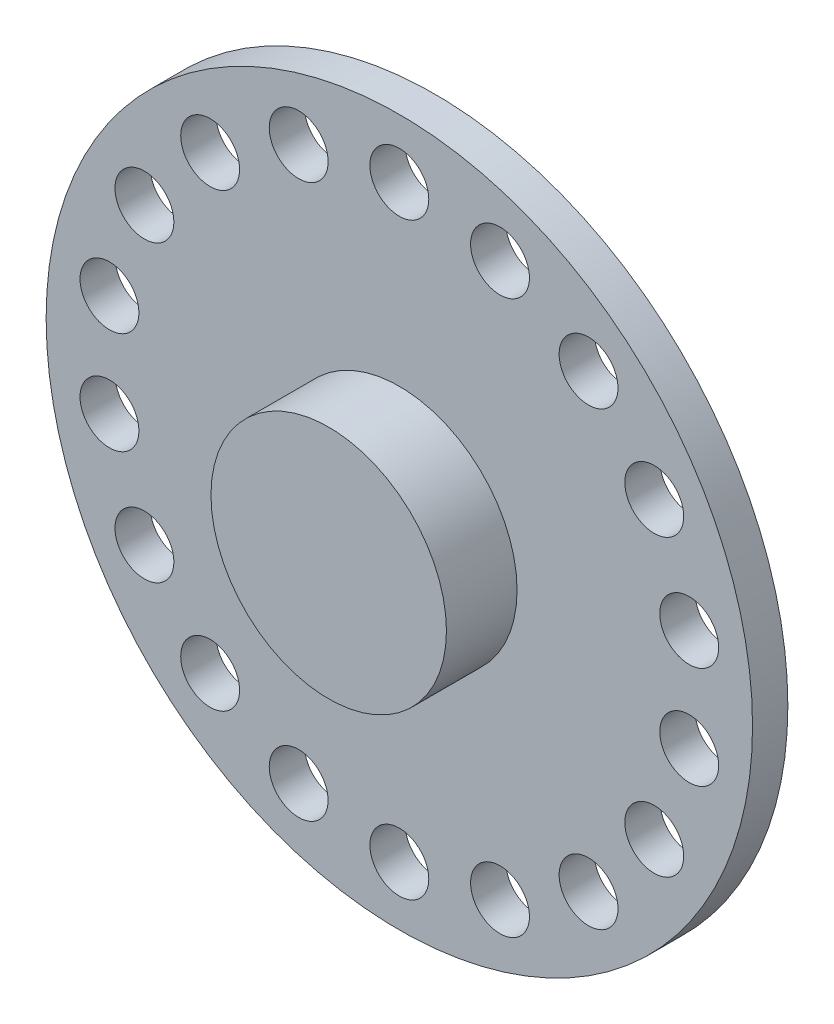
SolidWorks part; units mm, degrees
ref_plane "Front Plane" through (0, 0, 0) normal (0, 0, 1) x (1, 0, 0)
ref_plane "Top Plane" through (0, 0, 0) normal (0, 1, 0) x (1, 0, 0)
ref_plane "Right Plane" through (0, 0, 0) normal (1, 0, 0) x (0, 0, -1)
sketch "Sketch1" plane through (0, 0, 0) normal (0, 0, 1) x (1, 0, 0)
  circle A0 centre (0, 0) radius 30
  dimension "D1" = 60
extrude "Boss-Extrude1" add sketch "Sketch1" along normal blind 3
sketch "Sketch2" plane through (0, 0, 3) normal (0, 0, 1) x (1, 0, 0)
  circle A0 centre (0, 0) radius 10
  dimension "D1" = 20
extrude "Boss-Extrude2" add sketch "Sketch2" along normal blind 6
sketch "Sketch3" plane through (0, 0, 0) normal (0, 0, -1) x (-1, 0, 0)
  circle A0 centre (0, 25) radius 2.5
  circle A1 centre (8.5505, 23.4923) radius 2.5
  circle A2 centre (16.0697, 19.1511) radius 2.5
  circle A3 centre (21.6506, 12.5) radius 2.5
  circle A4 centre (24.6202, 4.3412) radius 2.5
  circle A5 centre (24.6202, -4.3412) radius 2.5
  circle A6 centre (21.6506, -12.5) radius 2.5
  circle A7 centre (16.0697, -19.1511) radius 2.5
  circle A8 centre (8.5505, -23.4923) radius 2.5
  circle A9 centre (0, -25) radius 2.5
  circle A10 centre (-8.5505, -23.4923) radius 2.5
  circle A11 centre (-16.0697, -19.1511) radius 2.5
  circle A12 centre (-21.6506, -12.5) radius 2.5
  circle A13 centre (-24.6202, -4.3412) radius 2.5
  circle A14 centre (-24.6202, 4.3412) radius 2.5
  circle A15 centre (-21.6506, 12.5) radius 2.5
  circle A16 centre (-16.0697, 19.1511) radius 2.5
  circle A17 centre (-8.5505, 23.4923) radius 2.5
  point P40 (0, 0)
  dimension "D1" = 5
  dimension "D2" = 25
  dimension "D3" = 18
extrude "Cut-Extrude1" cut sketch "Sketch3" against normal through all
